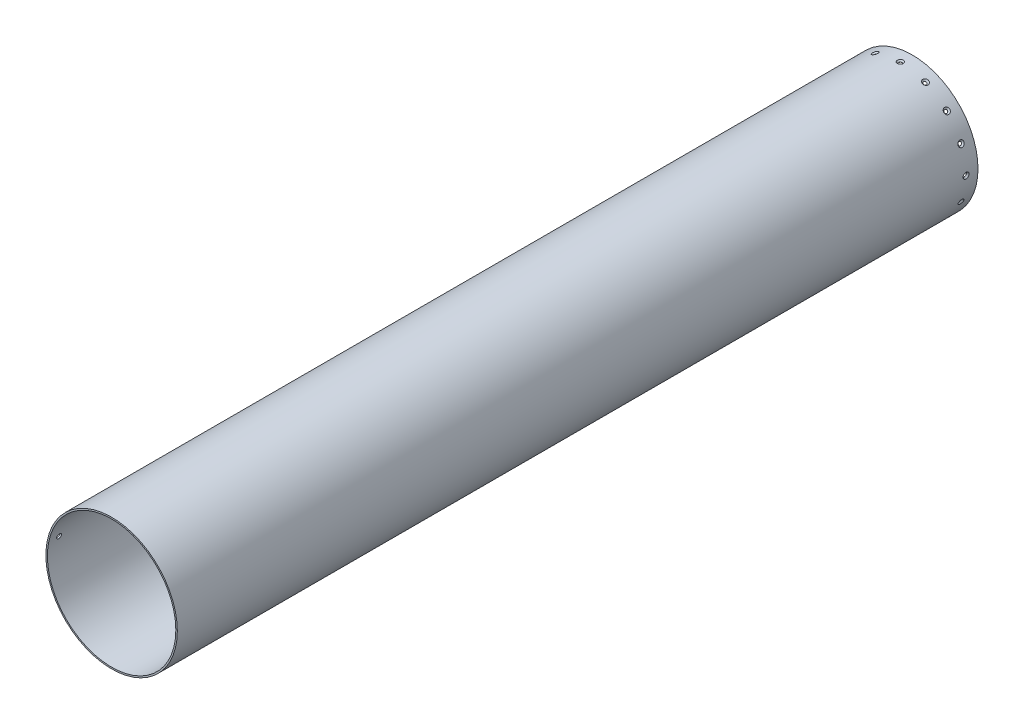
SolidWorks part; units mm, degrees
material "6061-T6 (SS)"
ref_plane "Front Plane" through (0, 0, 0) normal (0, 0, 1) x (1, 0, 0)
ref_plane "Top Plane" through (0, 0, 0) normal (0, 1, 0) x (1, 0, 0)
ref_plane "Right Plane" through (0, 0, 0) normal (1, 0, 0) x (0, 0, -1)
sketch "Sketch1" plane through (0, 0, 0) normal (0, 0, 1) x (1, 0, 0)
  circle A0 centre (0, 0) radius 69.85
  circle A1 centre (0, 0) radius 68.2625
  dimension "D1" = 139.7
  dimension "D2" = 1.5875
  dimension "D3" = 136.525
extrude "Extrude1" add sketch "Sketch1" along normal blind 850.9
ref_plane "Plane1" through (0, 0, 12.7) normal (0, 0, -1) x (-1, 0, 0)
sketch "Sketch2" plane through (0, 0, 12.7) normal (0, 0, -1) x (-1, 0, 0)
  line L0 (0, 0) -> (0, -69.85) construction
  circle A0 centre (0, 0) radius 69.85 construction
ref_plane "Plane2" through (0, -69.85, 12.7) normal (0, -1, 0) x (1, 0, 0)
hole_wizard "CSK for M3 Flat Head Machine Screw1" positions "Sketch5" profile "Sketch4" countersink size "M3" standard "Ansi Metric" end condition through all
sketch "Sketch5" plane through (0, -69.85, 12.7) normal (0, -1, 0) x (1, 0, 0)
  point P2 (0, 0)
sketch "Sketch4" plane through (0, -69.85, 12.7) normal (1, 0, 0) x (0, 0, -1)
  line L0 (0, 0) -> (0, 161.1134)
  line L1 (0, 161.1134) -> (1.7, 161.1134)
  line L2 (1.7, 161.1134) -> (1.7, 1.45)
  line L3 (1.7, 1.45) -> (3.15, 0)
  line L5 (3.15, 0) -> (0, 0)
  line L6 (-1.7, 1.45) -> (-3.15, 0) construction
  line L11 (0, -6.35) -> (0, 107.95) construction
  dimension "Thru Hole Dia." = 3.4
  dimension "Thru Hole Depth" = 161.1134
  dimension "Near C'Sink Dia." = 6.3
  dimension "Near C'Sink Angle" = 90
pattern_circular "CirPattern1" count 16 over 360 about axis through (0, 0, 850.9) along (0, 0, -1) of "CSK for M3 Flat Head Machine Screw1"
ref_plane "Plane3" through (0, 0, 839.7875) normal (0, 0, 1) x (1, 0, 0)
ref_plane "Plane5" through (0, 0, 0) normal (0.8315, 0.5556, 0) x (-0.5556, 0.8315, 0)
ref_plane "Plane7" through (0, 0, 0) normal (0.5556, -0.8315, 0) x (0.8315, 0.5556, 0)
ref_plane "Plane9" through (0, 0, 0) normal (-0.1951, -0.9808, 0) x (0.9808, -0.1951, 0)
sketch "Sketch7" plane through (0, 0, 850.9) normal (0, 0, 1) x (1, 0, 0)
  circle A0 centre (0, 0) radius 69.85 construction
  point P0 (69.85, 0)
ref_plane "Plane8" through (-68.5079, 13.6271, 425.45) normal (-0.9808, 0.1951, 0) x (0.1951, 0.9808, 0)
sketch "Sketch8" plane through (-68.5079, 13.6271, 425.45) normal (-0.9808, 0.1951, 0) x (0.1951, 0.9808, 0)
  line L0 (0, -425.45) -> (0, -414.3248) construction
hole_wizard "#7 (0.201) Diameter Hole1" positions "Sketch10" profile "Sketch9" hole size "#7" standard "Ansi Inch"
sketch "Sketch10" plane through (-68.5079, 13.6271, 425.45) normal (-0.9808, 0.1951, 0) x (0.1951, 0.9808, 0)
  point P1 (0, -414.3248)
sketch "Sketch9" plane through (-68.5079, 13.6271, 839.7748) normal (0, 0, 1) x (-0.1951, -0.9808, 0)
  line L0 (0, 0) -> (0, 11.6938)
  line L1 (0, 11.6938) -> (2.5527, 10.16)
  line L2 (2.5527, 10.16) -> (2.5527, 0)
  line L5 (2.5527, 0) -> (0, 0)
  line L10 (0, 11.6938) -> (-2.5527, 10.16) construction
  line L11 (0, -6.35) -> (0, 107.95) construction
  dimension "Hole Dia." = 5.1054
  dimension "Hole Depth" = 10.16
  dimension "Drill Angle" = 118
